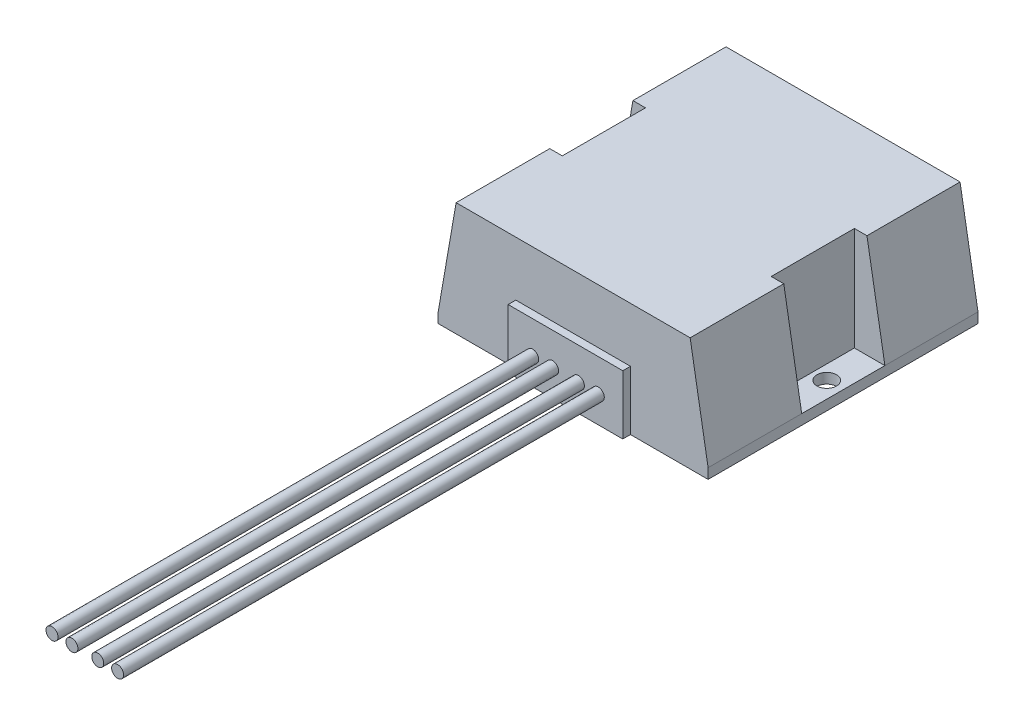
SolidWorks part; units mm, degrees
ref_plane "Front Plane" through (0, 0, 0) normal (0, 0, 1) x (1, 0, 0)
ref_plane "Top Plane" through (0, 0, 0) normal (0, 1, 0) x (1, 0, 0)
ref_plane "Right Plane" through (0, 0, 0) normal (1, 0, 0) x (0, 0, -1)
sketch "Sketch1" plane through (0, 0, 0) normal (0, 0, 1) x (1, 0, 0)
  line L0 (0, 0) -> (37.084, 0)
  line L1 (0, 0) -> (-37.084, 0)
  line L2 (0, 31.242) -> (32.1564, 31.242)
  line L3 (37.084, 0) -> (37.084, 2.794)
  line L4 (-37.084, 0) -> (-37.084, 2.794)
  line L5 (0, 31.242) -> (-32.1564, 31.242)
  line L6 (-32.1564, 31.242) -> (-37.084, 2.794)
  line L7 (32.1564, 31.242) -> (37.084, 2.794)
  dimension "D1" = 37.084
  dimension "D2" = 37.084
  dimension "D3" = 32.1564
  dimension "D4" = 2.794
  dimension "D5" = 2.794
  dimension "D6" = 32.1564
extrude "Boss-Extrude1" add sketch "Sketch1" along normal mid plane 74.168
sketch "Sketch2" plane through (0, 0, 0) normal (0, 1, 0) x (1, 0, 0)
  line L0 (32.1564, 37.084) -> (32.1564, 11.43) construction
  line L1 (32.1564, -37.084) -> (32.1564, 37.084) construction
  line L7 (37.084, -37.084) -> (37.084, 37.084) construction
  line L8 (37.084, 11.4985) -> (28.702, 11.4985)
  line L9 (37.084, 11.4985) -> (37.084, -11.3615)
  line L10 (37.084, -11.3615) -> (28.702, -11.3615)
  line L11 (28.702, 11.4985) -> (28.702, -11.3615)
  dimension "D1" = 25.654
  dimension "D2" = 22.86
  dimension "D3" = 8.382
extrude "Cut-Extrude1" cut sketch "Sketch2" along normal up to surface (28.448 mm away) from offset 2.794 up to face at (0, 31.242, 0)
sketch "Sketch4" plane through (0, 2.794, 0) normal (0, 1, 0) x (1, 0, 0)
  line L0 (37.084, -11.3615) -> (37.084, 0.0685) construction
  line L1 (37.084, -11.3615) -> (37.084, 11.4985) construction
  line L2 (37.084, 0.0685) -> (32.6141, 0) construction
  line L3 (0, 0) -> (37.084, 0) construction
  circle A0 centre (32.6141, 0) radius 2.6924
  dimension "D3" = 5.3848
  dimension "D1" = 11.43
  dimension "D2" = 4.4704
extrude "Cut-Extrude2" cut sketch "Sketch4" against normal through all
mirror "Mirror1" about plane through (0, 0, 0) normal (1, 0, 0) of "Cut-Extrude2"
mirror "Mirror2" about plane through (0, 0, 0) normal (1, 0, 0) of "Cut-Extrude1"
sketch "Sketch5" plane through (0, 0, 37.084) normal (0, 0, 1) x (1, 0, 0)
  line L0 (0, 0) -> (15.748, 0)
  line L1 (0, 0) -> (37.084, 0) construction
  line L2 (0, 0) -> (-15.748, 0)
  line L3 (0, 0) -> (-37.084, 0) construction
  line L4 (-15.748, 0) -> (-15.748, 16.256)
  line L5 (-15.748, 16.256) -> (15.748, 16.256)
  line L6 (15.748, 16.256) -> (15.748, 0)
  dimension "D1" = 15.748
  dimension "D2" = 15.748
  dimension "D3" = 16.256
extrude "Boss-Extrude2" add sketch "Sketch5" along normal blind 2.1082
sketch "Sketch6" plane through (0, 0, 39.1922) normal (0, 0, 1) x (1, 0, 0)
  line L0 (0, 0) -> (0, 7.366) construction
  line L1 (0, 7.366) -> (-3.556, 7.366) construction
  line L2 (-3.556, 7.366) -> (-9.017, 7.366) construction
  circle A0 centre (-3.556, 7.366) radius 1.651
  circle A1 centre (-9.017, 7.366) radius 1.651
  dimension "D3" = 3.302
  dimension "D5" = 3.302
  dimension "D1" = 7.366
  dimension "D2" = 3.556
  dimension "D4" = 5.461
extrude "Boss-Extrude3" add sketch "Sketch6" along normal blind 132.08 separate body
mirror "Mirror5" about plane through (0, 0, 0) normal (1, 0, 0) of "Boss-Extrude3"
